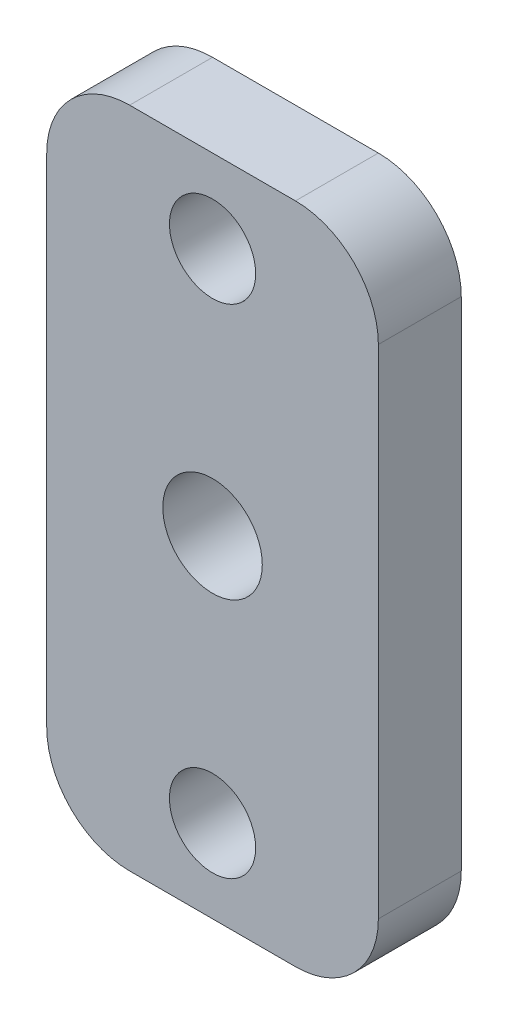
SolidWorks part; units mm, degrees
ref_plane "Plano frontal" through (0, 0, 0) normal (0, 0, 1) x (1, 0, 0)
ref_plane "Plano superior" through (0, 0, 0) normal (0, 1, 0) x (1, 0, 0)
ref_plane "Plano direito" through (0, 0, 0) normal (1, 0, 0) x (0, 0, -1)
sketch "Esboço1" plane through (0, 0, 0) normal (0, 0, 1) x (1, 0, 0)
  line L1 (-10, 20) -> (10, 20)
  line L2 (-10, 20) -> (-10, -20)
  line L3 (-10, -20) -> (10, -20)
  line L4 (10, 20) -> (10, -20)
  line L5 (-10, 20) -> (10, -20) construction
  line L6 (-10, -20) -> (10, 20) construction
  circle A0 centre (0, 0) radius 3
  point P0 (0, 0)
  dimension "D3" = 6
  dimension "D1" = 20
  dimension "D2" = 40
extrude "Ressalto-extrusão1" add sketch "Esboço1" along normal mid plane 5
fillet "Filete1" radius 5 4 edges at (10, -20, 0) (-10, -20, 0) (10, 20, 0) (-10, 20, 0)
sketch "Esboço2" plane through (0, 0, 2.5) normal (0, 0, 1) x (1, 0, 0)
  line L0 (0, 20) -> (0, -20) construction
  line L1 (5, 20) -> (-5, 20) construction
  line L2 (-5, -20) -> (5, -20) construction
  circle A0 centre (0, 15) radius 2.6
  circle A1 centre (0, 0) radius 3 construction
  dimension "D1" = 5.2
  dimension "D2" = 15
extrude "Corte-extrusão1" cut sketch "Esboço2" against normal blind 6
mirror "Espelhar1" about plane through (0, 0, 0) normal (0, 1, 0) of "Corte-extrusão1"
